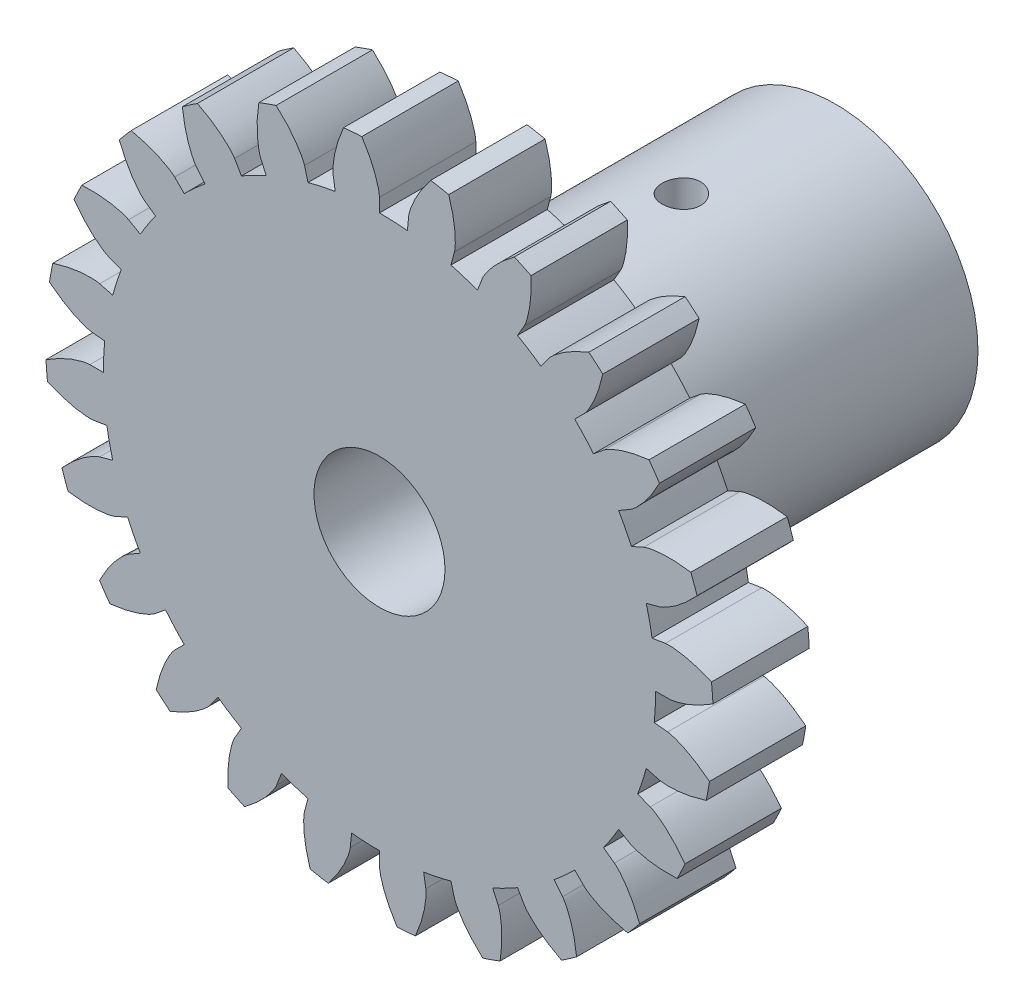
SolidWorks part; units mm, degrees
material "7075-O (SS)"
ref_plane "Front" through (0, 0, 0) normal (0, 0, 1) x (1, 0, 0)
ref_plane "Top" through (0, 0, 0) normal (0, 1, 0) x (1, 0, 0)
ref_plane "Right" through (0, 0, 0) normal (1, 0, 0) x (0, 0, -1)
sketch "ｽｹｯﾁ1" plane through (0, 0, 0) normal (0, 0, 1) x (1, 0, 0)
  line L0 (22.5526, 0) -> (0, 0) construction
  line L1 (22.5526, 0) -> (21.5, 0)
  line L2 (0, 0) -> (25.9668, -1.3136)
  circle A0 centre (0, 0) radius 22.5526 construction
  circle A1 centre (0, 0) radius 21.5 construction
  circle A2 centre (0, 0) radius 24 construction
  circle A3 centre (0, 0) radius 26
  arc A4 (21.5, 0) -> (21.4725, -1.0863) centre (0, 0) cw
  arc A5 (23.9973, 0.3577) -> (23.9693, -1.2126) centre (0, 0) cw
  spline S0 degree 4 poles (22.5526, 0) (22.5874, 0.0011) (22.6567, 0.0054) (22.8505, 0.0283) (23.2156, 0.0999) (23.764, 0.2576) (24.4933, 0.5458) (25.3932, 1.0005) (26.3919, 1.6314) (27.421, 2.4222) (28.4509, 3.3688) (29.4028, 4.3935) (30.2783, 5.4838) (31.1188, 6.6866) (32.0583, 8.2419) (33.024, 10.183) (33.9312, 12.5326) (34.6768, 15.2302) (35.1717, 17.9843) (35.4277, 20.7703) (35.4563, 23.5676) (35.2683, 26.3585) (34.9241, 28.7814) (34.5417, 30.6653) (34.2091, 32.0222) (33.9364, 33.0347) (33.6419, 34.0391) (33.318, 35.0387) (32.9699, 36.023) (32.6584, 36.8453) (32.4056, 37.4843) (32.1525, 38.0917) (31.9408, 38.5845) (31.6913, 39.1427) (31.5261, 39.5026) (31.2539, 40.0814) (31.0342, 40.5277) (30.7638, 41.0681) (30.5147, 41.5456) (30.242, 42.0581) (29.9755, 42.5406) (29.7632, 42.9175) (29.6249, 43.1564) (29.5531, 43.2804) knots 0 0 0 0 0 0.002802 0.005604 0.015718 0.02996 0.048734 0.068727 0.096889 0.125051 0.153212 0.181374 0.209535 0.237696 0.271429 0.327752 0.384075 0.440398 0.496721 0.553044 0.609367 0.66569 0.722013 0.750174 0.764255 0.778336 0.806497 0.834659 0.84874 0.86282 0.876901 0.890982 0.900036 0.909091 0.920455 0.931818 0.943182 0.954545 0.965909 0.977273 0.988636 1 1 1 1 1 construction
  spline S1 degree 4 poles (22.5526, 0) (22.5874, 0.0011) (22.6567, 0.0054) (22.8505, 0.0283) (23.2156, 0.0999) (23.764, 0.2576) (24.4933, 0.5458) (25.3932, 1.0005) (26.3919, 1.6314) (27.421, 2.4222) (28.4509, 3.3688) (29.4028, 4.3935) (30.2783, 5.4838) (31.1188, 6.6866) (32.0583, 8.2419) (33.024, 10.183) (33.9312, 12.5326) (34.6768, 15.2302) (35.1717, 17.9843) (35.4277, 20.7703) (35.4563, 23.5676) (35.2683, 26.3585) (34.9241, 28.7814) (34.5417, 30.6653) (34.2091, 32.0222) (33.9364, 33.0347) (33.6419, 34.0391) (33.318, 35.0387) (32.9699, 36.023) (32.6584, 36.8453) (32.4056, 37.4843) (32.1525, 38.0917) (31.9408, 38.5845) (31.7564, 38.9971) (31.6714, 39.1846) (31.6289, 39.2774) knots 0 0 0 0 0 0.002802 0.005604 0.015718 0.02996 0.048734 0.068727 0.096889 0.125051 0.153212 0.181374 0.209535 0.237696 0.271429 0.327752 0.384075 0.440398 0.496721 0.553044 0.609367 0.66569 0.722013 0.750174 0.764255 0.778336 0.806497 0.834659 0.84874 0.86282 0.876901 0.890982 0.900036 0.909091 0.909091 0.909091 0.909091 0.909091
  dimension "歯先円直径" = 52
  dimension "基礎円直径" = 45.1052
  dimension "基礎ピッチ円直径" = 48
  dimension "全歯たけ" = 4.5
  dimension "基準ピッチ/4" = 1.5708
sketch "ｽｹｯﾁ3" plane through (0, 0, 0) normal (0, 0, 1) x (1, 0, 0)
  circle A0 centre (0, 0) radius 26 construction
  circle A1 centre (0, 0) radius 26
extrude "ﾎﾞｽ - 押し出し2" add sketch "ｽｹｯﾁ3" along normal blind 7.5
sketch "ｽｹｯﾁ4" plane through (0, 0, 0) normal (0, 0, 1) x (1, 0, 0)
  line L0 (0, 0) -> (25.9668, -1.3136) construction
  line L1 (22.5526, 0) -> (21.5, 0) construction
  line L2 (21.4725, -1.0863) -> (25.9668, -1.3136)
  line L3 (22.5526, 0) -> (21.5, 0)
  arc A1 (21.4725, -1.0863) -> (21.5, 0) centre (0, 0) ccw construction
  circle A2 centre (0, 0) radius 26 construction
  arc A3 (21.4725, -1.0863) -> (21.5, 0) centre (0, 0) ccw
  arc A4 (25.9668, -1.3136) -> (25.9637, 1.373) centre (0, 0) ccw
  spline S1 degree 4 poles (15.1862, -999.773) (16.9514, 36.3954) (19.0933, 0.7282) (21.1742, -0.3006) (23.2156, 0.0999) (23.764, 0.2576) (24.4933, 0.5458) (25.3932, 1.0005) (26.3919, 1.6314) (27.421, 2.4222) (28.4509, 3.3688) (29.4028, 4.3935) (30.2783, 5.4838) (31.1188, 6.6866) (32.0583, 8.2419) (33.024, 10.183) (33.9312, 12.5326) (34.6768, 15.2302) (35.1717, 17.9843) (35.4277, 20.7703) (35.4563, 23.5676) (35.2683, 26.3585) (34.9241, 28.7814) (34.5417, 30.6653) (34.2091, 32.0222) (33.9364, 33.0347) (33.6419, 34.0391) (33.318, 35.0387) (32.9699, 36.023) (32.6584, 36.8453) (32.4056, 37.4843) (32.1525, 38.0917) (31.3467, 39.9673) (29.663, 43.4627) (43.99, 11.7586) (-384.9057, 948.343) knots -0.13757 -0.13757 -0.13757 -0.13757 -0.13757 0.002802 0.005604 0.015718 0.02996 0.048734 0.068727 0.096889 0.125051 0.153212 0.181374 0.209535 0.237696 0.271429 0.327752 0.384075 0.440398 0.496721 0.553044 0.609367 0.66569 0.722013 0.750174 0.764255 0.778336 0.806497 0.834659 0.84874 0.86282 0.876901 0.890982 0.900036 1.038953 1.038953 1.038953 1.038953 1.038953 only from (22.5526, 0) to (31.6289, 39.2774) construction
  spline S2 degree 4 poles (22.5526, 0) (22.5874, 0.0011) (22.6567, 0.0054) (22.8505, 0.0283) (23.2156, 0.0999) (23.764, 0.2576) (24.4933, 0.5458) (25.1482, 0.8767) (25.6277, 1.1589) (25.9005, 1.3322) (25.9637, 1.373) knots 0 0 0 0 0 0.002802 0.005604 0.015718 0.02996 0.048734 0.068727 0.074792 0.074792 0.074792 0.074792 0.074792
extrude "ｶｯﾄ - 押し出し2" cut sketch "ｽｹｯﾁ4" along normal through all
pattern_circular "円形ﾊﾟﾀｰﾝ1" count 24 over 360 about axis through (0, 0, 7.5) along (0, 0, -1) of "ｶｯﾄ - 押し出し2"
mirror "ﾐﾗｰ1" about plane through (21.4725, -1.0863, 7.5) normal (0.0505, 0.9987, 0) of "円形ﾊﾟﾀｰﾝ1", "ｶｯﾄ - 押し出し2"
sketch "ｽｹｯﾁ5" plane through (0, 0, 7.5) normal (0, 0, 1) x (1, 0, 0)
  circle A0 centre (0, 0) radius 5.1
  dimension "D1" = 10.2
extrude "ｶｯﾄ - 押し出し3" cut sketch "ｽｹｯﾁ5" against normal through all
sketch "ｽｹｯﾁ7" plane through (0, 0, 0) normal (0, 0, -1) x (-1, 0, 0)
  circle A0 centre (0, 0) radius 11.1
  circle A1 centre (0, 0) radius 5.1
  circle A2 centre (0, 0) radius 5.1 construction
  dimension "D1" = 6
extrude "ﾎﾞｽ - 押し出し3" add sketch "ｽｹｯﾁ7" along normal blind 28
sketch "ｽｹｯﾁ8" plane through (0, 0, 0) normal (0, 1, 0) x (1, 0, 0)
  line L0 (0, 0) -> (0, 28) construction
  line L1 (5.1, 28) -> (-5.1, 28) construction
  line L2 (0, 0) -> (0, -7.5) construction
  line L3 (-15.2028, -7.5) -> (-13.5909, -7.5) construction
  circle A0 centre (0, 16) radius 1.5
  dimension "D1" = 3
  dimension "D2" = 23.5
extrude "ｶｯﾄ - 押し出し4" cut sketch "ｽｹｯﾁ8" against normal through all both and the other way through all
equation "\"モジュール\"= 2"
equation "\"歯数\"= 24"
equation "\"圧力角\"= 20"
equation "\"歯幅\"= 7.5"
equation "\"D1@ﾎﾞｽ - 押し出し2\"=\"歯幅\""
equation "\"D1@円形ﾊﾟﾀｰﾝ1\"=\"歯数\""
equation "\"歯先円直径@ｽｹｯﾁ1\"=(\"歯数\"+2)*(\"モジュール\")"
equation "\"基礎円直径@ｽｹｯﾁ1\"=\"歯数\"*\"モジュール\"*cos(\"圧力角\")"
equation "\"全歯たけ@ｽｹｯﾁ1\"= \"モジュール\" * 2.25"
equation "\"基礎ピッチ円直径@ｽｹｯﾁ1\"=\"歯数\"*\"モジュール\""
equation "\"基準ピッチ/4@ｽｹｯﾁ1\" = PI * \"モジュール\" / 4"
